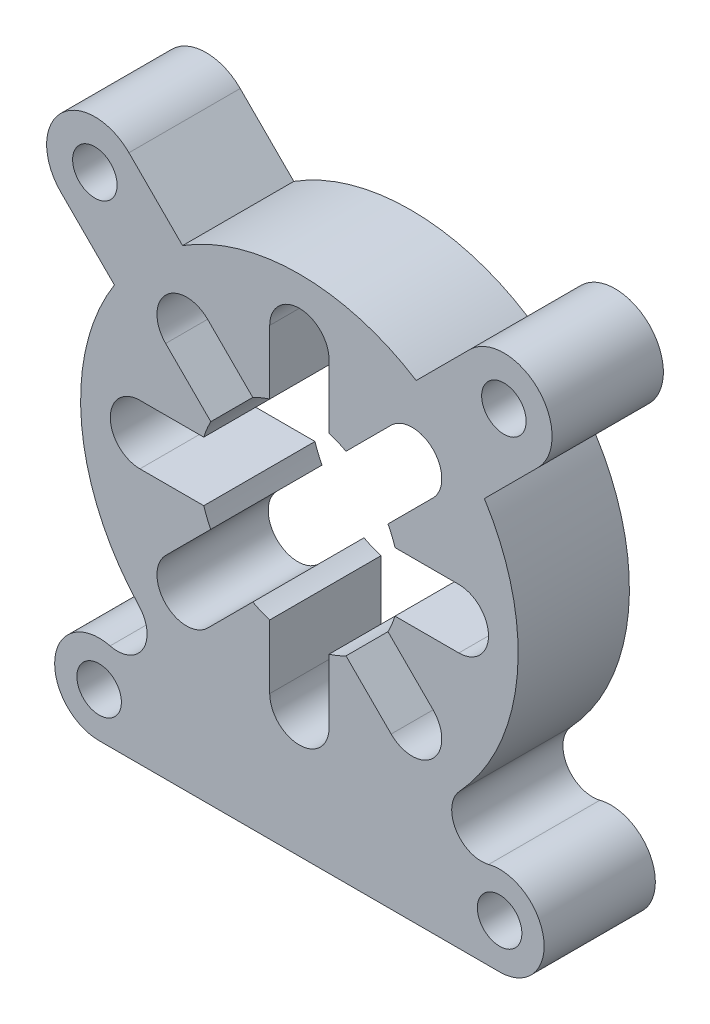
SolidWorks part; units mm, degrees
ref_plane "Alzado" through (0, 0, 0) normal (0, 0, 1) x (1, 0, 0)
ref_plane "Planta" through (0, 0, 0) normal (0, 1, 0) x (1, 0, 0)
ref_plane "Vista lateral" through (0, 0, 0) normal (1, 0, 0) x (0, 0, -1)
sketch "Croquis1" plane through (0, 0, 0) normal (0, 0, 1) x (1, 0, 0)
  line L0 (0, 0) -> (0, 76.145) construction
  line L1 (0, 0) -> (-55.1543, 55.1543) construction
  line L2 (24.7487, 36.0624) -> (12.5777, 23.8914)
  line L4 (-8, 43) -> (-8, 25.7876)
  line L6 (8, 43) -> (8, 25.7876)
  line L7 (36.0624, 24.7487) -> (23.8914, 12.5777)
  line L8 (43, 8) -> (25.7876, 8)
  line L9 (43, -8) -> (25.7876, -8)
  line L10 (36.0624, -24.7487) -> (23.8914, -12.5777)
  line L11 (24.7487, -36.0624) -> (12.5777, -23.8914)
  line L12 (8, -43) -> (8, -25.7876)
  line L13 (-8, -43) -> (-8, -25.7876)
  line L14 (-24.7487, -36.0624) -> (-12.5777, -23.8914)
  line L15 (-36.0624, -24.7487) -> (-23.8914, -12.5777)
  line L16 (-43, -8) -> (-25.7876, -8)
  line L17 (-43, 8) -> (-25.7876, 8)
  line L18 (-36.0624, 24.7487) -> (-23.8914, 12.5777)
  line L19 (-24.7487, 36.0624) -> (-12.5777, 23.8914)
  line L20 (-64.3467, 45.9619) -> (-49.8864, 31.5016)
  line L21 (-45.9619, 64.3467) -> (-31.5016, 49.8864)
  line L22 (-54, -77) -> (0.0093, -77)
  line L23 (54, -77) -> (-0.0093, -77)
  line L24 (64.3467, 45.9619) -> (49.8864, 31.5016)
  line L25 (45.9619, 64.3467) -> (31.5016, 49.8864)
  arc A0 (-8, 25.7876) -> (-12.5777, 23.8914) centre (0, 0) ccw
  circle A1 centre (0, 0) radius 43 construction
  arc A2 (-49.8864, 31.5016) -> (49.8864, 31.5016) centre (0, 0) ccw
  circle A3 centre (0, 0) radius 78 construction
  arc A4 (-45.9619, 64.3467) -> (-64.3467, 45.9619) centre (-55.1543, 55.1543) ccw
  arc A5 (-51.0437, -53.3699) -> (-54, -77) centre (-54, -65) ccw
  arc A6 (8, 43) -> (-8, 43) centre (0, 43) ccw
  arc A7 (36.0624, 24.7487) -> (24.7487, 36.0624) centre (30.4056, 30.4056) ccw
  arc A8 (43, -8) -> (43, 8) centre (43, 0) ccw
  arc A9 (24.7487, -36.0624) -> (36.0624, -24.7487) centre (30.4056, -30.4056) ccw
  arc A10 (-8, -43) -> (8, -43) centre (0, -43) ccw
  arc A11 (-36.0624, -24.7487) -> (-24.7487, -36.0624) centre (-30.4056, -30.4056) ccw
  arc A12 (-43, 8) -> (-43, -8) centre (-43, 0) ccw
  arc A13 (-24.7487, 36.0624) -> (-36.0624, 24.7487) centre (-30.4056, 30.4056) ccw
  arc A14 (-23.8914, 12.5777) -> (-25.7876, 8) centre (0, 0) ccw
  arc A15 (-25.7876, -8) -> (-23.8914, -12.5777) centre (0, 0) ccw
  arc A16 (-12.5777, -23.8914) -> (-8, -25.7876) centre (0, 0) ccw
  arc A17 (8, -25.7876) -> (12.5777, -23.8914) centre (0, 0) ccw
  arc A18 (23.8914, -12.5777) -> (25.7876, -8) centre (0, 0) ccw
  arc A19 (25.7876, 8) -> (23.8914, 12.5777) centre (0, 0) ccw
  arc A20 (12.5777, 23.8914) -> (8, 25.7876) centre (0, 0) ccw
  circle A21 centre (-55.1543, 55.1543) radius 6
  arc A22 (-43.2134, -40.1697) -> (-51.0437, -53.3699) centre (-49.0728, -45.6164) cw
  circle A23 centre (-54, -65) radius 6
  circle A24 centre (54, -65) radius 6
  arc A25 (51.0437, -53.3699) -> (54, -77) centre (54, -65) cw
  arc A26 (43.2134, -40.1697) -> (51.0437, -53.3699) centre (49.0728, -45.6164) ccw
  circle A27 centre (55.1543, 55.1543) radius 6
  arc A28 (45.9619, 64.3467) -> (64.3467, 45.9619) centre (55.1543, 55.1543) cw
  arc A29 (31.5016, 49.8864) -> (-31.5016, 49.8864) centre (0, 0) ccw
  point P54 (0, 0)
  dimension "D2" = 54
  dimension "D3" = 86
  dimension "D4" = 118
  dimension "D5" = 156
  dimension "D8" = 8
  dimension "D10" = 13
  dimension "D11" = 8
  dimension "D12" = 12
  dimension "D13" = 12
  dimension "D1" = 45
  dimension "D6" = 65
  dimension "D7" = 54
  dimension "D9" = 8
extrude "Saliente-Extruir2" add sketch "Croquis1" along normal blind 30 contours L25 A29 L21 A4 L20 A2 L24 A28 A27 A21 A20 L2 A7 L7 A19 L8 A8 L9 A18 L10 A9 L11 A17 L12 A10 L13 A16 L14 A11 L15 A15 L16 A12 L17 A14 L18 A13 L19 A0 L4 A6 L6 | A26 A2 A22 A5 L22 L23 A25 A23 A24
